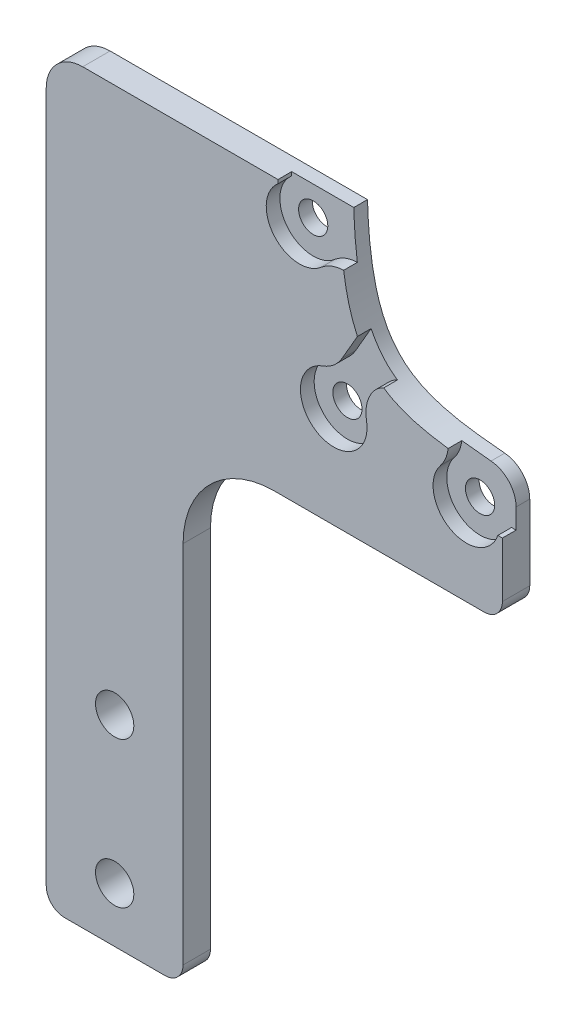
SolidWorks part; units mm, degrees
ref_plane "Front Plane" through (0, 0, 0) normal (0, 0, 1) x (1, 0, 0)
ref_plane "Top Plane" through (0, 0, 0) normal (0, 1, 0) x (1, 0, 0)
ref_plane "Right Plane" through (0, 0, 0) normal (1, 0, 0) x (0, 0, -1)
sketch "Sketch8" plane through (0, 0, 0) normal (0, 0, 1) x (1, 0, 0)
  line L7 (-4.8481, -13.3215) -> (-4.8481, -0.3215)
  line L12 (-4.8481, -13.3215) -> (-39.8481, -13.3215)
  line L16 (-39.8481, -13.3215) -> (-39.8481, -65.3215)
  line L17 (-39.8481, -65.3215) -> (-54.8481, -65.3215)
  line L18 (-54.8481, -65.3215) -> (-54.8481, 16.4457)
  line L24 (-54.8481, 16.4457) -> (-22.6343, 16.4457)
  spline S0 degree 3 poles (-22.6343, 16.4457) (-22.4429, 9.9943) (-20.1262, 0.8763) (-11.5337, 0.191) (-4.8481, -0.3215) knots 0 0 0 0 0.444536 1 1 1 1
  dimension "D2" = 15
  dimension "D3" = 35
  dimension "D6" = 13
extrude "Boss-Extrude3" add sketch "Sketch8" against normal blind 3
sketch "Sketch1" [suppressed] plane through (0, 0, 0) normal (0, 0, 1) x (1, 0, 0)
  line L8 (-6.5579, 0.7698) -> (-6.5579, 5.0621)
  line L9 (-18.333, 10.0628) -> (-6.5579, 5.0621)
  line L12 (-10.508, 2.7378) -> (-10.508, 0.7698)
  line L13 (-18.333, 10.0628) -> (-22.4339, 2.9597)
  line L15 (-19.2729, 1.1347) -> (-19.2134, 1.2378)
  line L18 (-16.6153, 2.7378) -> (-10.508, 2.7378)
  line L19 (-23.333, 1.4026) -> (-20.172, -0.4224) construction
  arc A6 (-24.5568, 1.1913) -> (-19.743, -1.588) centre (-23.333, -2.2474) ccw
  arc A7 (-11.3838, -1.7281) -> (-5.6821, -1.7281) centre (-8.533, -4.0074) ccw
  arc A9 (-16.6153, 2.7378) -> (-19.2134, 1.2378) centre (-16.6153, -0.2622) ccw
  arc A10 (-22.4339, 2.9597) -> (-24.5568, 1.1913) centre (-25.898, 4.9597) cw
  arc A11 (-19.743, -1.588) -> (-19.2729, 1.1347) centre (-15.8088, -0.8653) cw
  arc A12 (-5.6821, -1.7281) -> (-6.5579, 0.7698) centre (-2.5579, 0.7698) cw
  arc A13 (-10.508, 0.7698) -> (-11.3838, -1.7281) centre (-14.508, 0.7698) cw
  point P3 (-18.4773, 2.8128)
  point P13 (-6.5579, -0.9379)
  point P19 (-10.508, -0.9379)
  dimension "D18" = 7.25
  dimension "D27" = 3.65
  dimension "D28" = 3.65
  dimension "D4" = 3
  dimension "D5" = 4
  dimension "D15" = 3.65
  dimension "D23" = 0
  dimension "D24" = 6
  dimension "D25" = 30
  dimension "D26" = 10
  dimension "D29" = 3.0695
  dimension "D31" = 1.76
fillet "Fillet1" radius 2 3 edges at (-4.8481, -13.3215, -1.5) (-54.8481, -65.3215, -1.5) (-39.8481, -65.3215, -1.5)
sketch "Sketch9" [suppressed] plane through (0, 0, 0) normal (0, 0, 1) x (1, 0, 0)
  circle A0 centre (-23.333, -2.2474) radius 1.6
  circle A1 centre (-8.533, -4.0074) radius 1.6
  arc A2 (-24.5568, 1.1913) -> (-19.743, -1.588) centre (-23.333, -2.2474) ccw construction
  arc A3 (-11.3838, -1.7281) -> (-5.6821, -1.7281) centre (-8.533, -4.0074) ccw construction
  dimension "D1" = 3.2
  dimension "D2" = 3.2
extrude "Cut-Extrude2" [suppressed] cut sketch "Sketch9" against normal blind 3
sketch "Sketch12" plane through (0, 0, 0) normal (0, 0, 1) x (1, 0, 0)
  line L2 (-52.8481, -65.3215) -> (-41.8481, -65.3215) construction
  line L3 (-54.8481, 16.4457) -> (-54.8481, -63.3215) construction
  circle A2 centre (-47.3481, -43.3215) radius 2.1
  circle A3 centre (-47.3481, -59.3215) radius 2.1
  dimension "D2" = 4.2
  dimension "D3" = 0
  dimension "D4" = 4.2
  dimension "D7" = 16
  dimension "D11" = 6
  dimension "D12" = 7.5
extrude "Cut-Extrude5" cut sketch "Sketch12" against normal blind 10
fillet "Fillet5" radius 4 1 edges at (-54.8481, 16.4457, -1.5)
fillet "Fillet6" radius 3 1 edges at (-4.8481, -0.3215, -1.5)
fillet "Fillet7" radius 10 1 edges at (-39.8481, -13.3215, -1.5)
extrude "Cut-Extrude6" [suppressed] cut sketch "Sketch1" against normal blind 10
sketch "Sketch14" plane through (0, 0, 0) normal (0, 0, 1) x (1, 0, 0)
  line L1 (-6.7839, 0.3592) -> (-3.9573, 0.3592)
  line L2 (-6.7839, 0.3592) -> (-6.7839, -5.8411)
  line L3 (-6.7839, -5.8411) -> (-3.9573, -5.8411)
  line L4 (-3.9573, 0.3592) -> (-3.9573, -5.8411)
extrude "Cut-Extrude8" [suppressed] cut sketch "Sketch14" against normal blind 10
sketch "Sketch16" plane through (0, 0, 0) normal (0, 0, 1) x (1, 0, 0)
  line L0 (-9.1002, 21.3162) -> (-9.2096, 22.5662)
  line L1 (-9.1002, 21.3162) -> (-8.2502, 21.3162)
  line L2 (-8.2502, 21.3162) -> (-8.1407, 22.568)
  line L4 (-9.2096, 22.5662) -> (-11.6407, 22.5662)
  line L5 (-11.6407, 24.5662) -> (-8.1407, 24.5662)
  line L8 (-6.8209, 0.6802) -> (-6.8209, 4.9725)
  line L9 (-11.8209, 4.9725) -> (-6.8209, 4.9725)
  line L10 (-8.1407, 24.5662) -> (-8.1407, 22.568)
  line L12 (-10.7709, 2.7232) -> (-10.7709, 0.6802)
  line L13 (-19.6837, 7.7232) -> (-22.4339, 2.9597)
  line L15 (-19.2729, 1.1347) -> (-19.2219, 1.2232)
  line L17 (-14.8558, 2.7232) -> (-16.6238, 2.7232)
  line L18 (-12.604, 2.7232) -> (-10.7709, 2.7232)
  line L19 (-23.333, 1.4026) -> (-20.172, -0.4224) construction
  line L20 (-20.9762, 15.0803) -> (-22.1264, 15.0803)
  line L21 (-20.932, 11.4303) -> (-22.1264, 11.4303)
  line L22 (-23.9245, 15.0803) -> (-23.9245, 11.4303) construction
  arc A0 (-11.8209, 4.9725) -> (-14.8372, 6.0417) centre (-13.7299, 4.3762) ccw
  arc A5 (-16.4412, 11.3657) -> (-15.9245, 14.7567) centre (-17.1999, 13.2162) ccw
  arc A6 (-24.5568, 1.1913) -> (-19.743, -1.588) centre (-23.333, -2.2474) ccw
  arc A7 (-11.6467, -1.8177) -> (-5.9451, -1.8177) centre (-8.7959, -4.097) ccw
  arc A8 (-12.604, 2.7232) -> (-14.8558, 2.7232) centre (-13.7299, 4.3762) cw
  arc A9 (-24.7194, 16.0346) -> (-24.7194, 10.4761) centre (-27.0854, 13.2553) ccw
  arc A10 (-20.9762, 15.0803) -> (-17.2228, 17.6976) centre (-20.9762, 19.0803) ccw
  arc A11 (-22.1264, 11.4303) -> (-24.7194, 10.4761) centre (-22.1264, 7.4303) ccw
  arc A12 (-22.1264, 15.0803) -> (-24.7194, 16.0346) centre (-22.1264, 19.0803) cw
  arc A13 (-22.4339, 2.9597) -> (-24.5568, 1.1913) centre (-25.898, 4.9597) cw
  arc A14 (-19.743, -1.588) -> (-19.2729, 1.1347) centre (-15.8088, -0.8653) cw
  arc A15 (-5.9451, -1.8177) -> (-6.8209, 0.6802) centre (-2.8209, 0.6802) cw
  arc A16 (-10.7709, 0.6802) -> (-11.6467, -1.8177) centre (-14.7709, 0.6802) cw
  arc A17 (-16.6238, 2.7232) -> (-19.2219, 1.2232) centre (-16.6238, -0.2768) ccw
  spline S0 degree 3 poles (-11.6407, 24.5662) (-14.2443, 22.933) (-16.1842, 20.5166) (-17.2228, 17.6976) knots 0 0 0 0 0.77321 0.77321 0.77321 0.77321
  spline S1 degree 2 poles (-11.6407, 22.5662) (-15.0225, 19.3404) (-15.9245, 14.7567) knots 0 0 0 1 1 1
  spline S2 degree 3 poles (-19.6837, 7.7232) (-19.2612, 8.548) (-18.9245, 9.5211) (-19.23, 11.0753) (-20.3586, 11.4237) (-20.932, 11.4303) knots 0 0 0 0 0.295584 0.638507 1 1 1 1
  spline S3 degree 2 poles (-14.8372, 6.0417) (-16.4592, 8.4762) (-16.4412, 11.3657) knots 0 0 0 1 1 1
  point P55 (-6.8209, -1.0275)
  point P58 (-10.7709, -1.0275)
  point P62 (-18.3558, 2.7232)
  dimension "D17" = 2
  dimension "D18" = 5
  dimension "D19" = 3.5
  dimension "D20" = 9.35
  dimension "D7" = 3.65
  dimension "D8" = 2
  dimension "D9" = 3.65
  dimension "D27" = 3.65
  dimension "D28" = 3.65
  dimension "D10" = 2
  dimension "D12" = 4
  dimension "D26" = 4
  dimension "D30" = 4
  dimension "D32" = 3
  dimension "D1" = 265
  dimension "D2" = 265
  dimension "D3" = 0.85
  dimension "D4" = 1.25
  dimension "D5" = 8.84
  dimension "D6" = 3.47
  dimension "D11" = 2
  dimension "D13" = 2
  dimension "D14" = 3.5
  dimension "D15" = 3.65
  dimension "D16" = 2
  dimension "D21" = 2.2493
  dimension "D22" = 5
  dimension "D23" = 0
  dimension "D24" = 6
  dimension "D25" = 30
  dimension "D29" = 3.0695
  dimension "D31" = 1.8496
extrude "Cut-Extrude9" cut sketch "Sketch16" against normal blind 1.5
sketch "Sketch17" plane through (0, 0, 0) normal (0, 0, 1) x (1, 0, 0)
  line L1 (-29.4444, 18.3942) -> (-21.4928, 18.3942)
  line L2 (-29.4444, 18.3942) -> (-29.4444, 13.1216)
  line L3 (-29.4444, 13.1216) -> (-21.4928, 13.1216)
  line L4 (-21.4928, 18.3942) -> (-21.4928, 13.1216)
  line L5 (-7.3457, 0.9041) -> (-3.4516, 0.9041)
  line L6 (-7.3457, 0.9041) -> (-7.3457, -5.2917)
  line L7 (-7.3457, -5.2917) -> (-3.4516, -5.2917)
  line L8 (-3.4516, 0.9041) -> (-3.4516, -5.2917)
extrude "Cut-Extrude10" cut sketch "Sketch17" against normal blind 1.5
sketch "Sketch18" plane through (0, 0, -1.5) normal (0, 0, 1) x (1, 0, 0)
  circle A0 centre (-27.0854, 13.2553) radius 1.6
  circle A1 centre (-23.333, -2.2474) radius 1.6
  circle A2 centre (-8.7959, -4.097) radius 1.6
  arc A3 (-29.4444, 16.0406) -> (-24.7194, 10.4761) centre (-27.0854, 13.2553) ccw construction
  arc A4 (-24.5568, 1.1913) -> (-19.743, -1.588) centre (-23.333, -2.2474) ccw construction
  arc A5 (-11.6467, -1.8177) -> (-5.347, -5.2917) centre (-8.7959, -4.097) ccw construction
  dimension "D4" = 3.2
  dimension "D5" = 3.2
  dimension "D6" = 3.2
  dimension "D1" = 0
  dimension "D2" = 0
  dimension "D3" = 0
extrude "Cut-Extrude11" cut sketch "Sketch18" against normal blind 10
